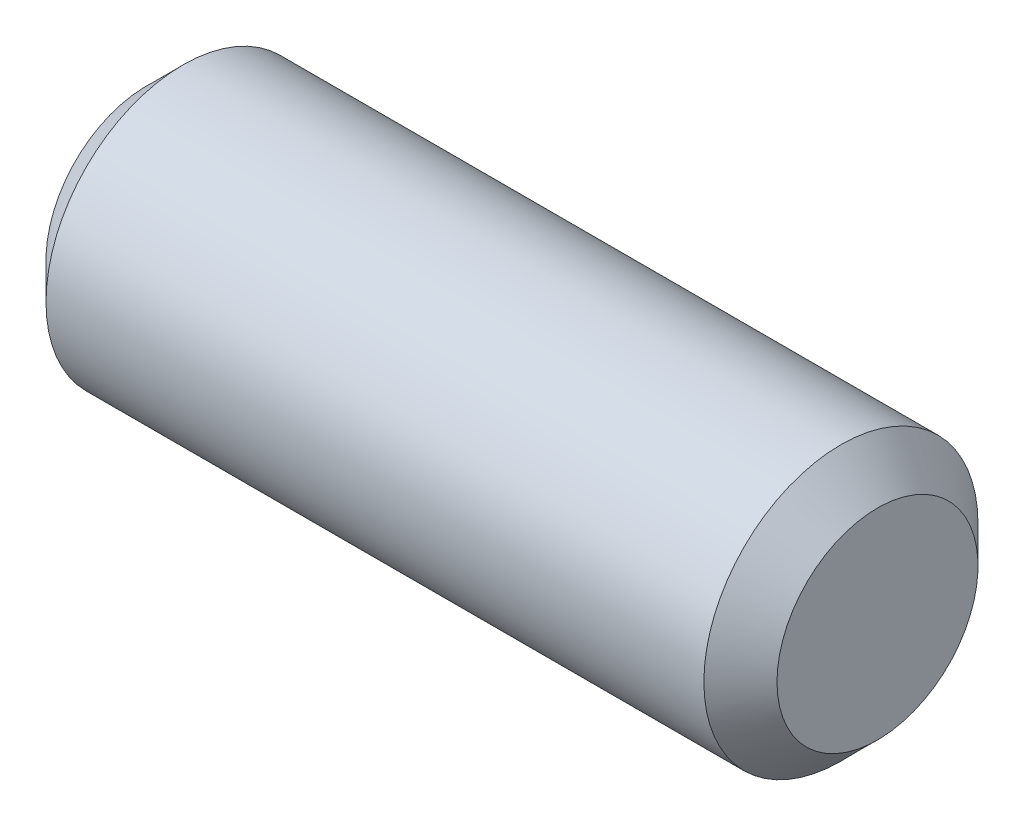
SolidWorks part; units mm, degrees
ref_plane "前视基准面" through (0, 0, 0) normal (0, 0, 1) x (1, 0, 0)
ref_plane "上视基准面" through (0, 0, 0) normal (0, 1, 0) x (1, 0, 0)
ref_plane "右视基准面" through (0, 0, 0) normal (1, 0, 0) x (0, 0, -1)
sketch "草图1" plane through (0, 0, 0) normal (0, 0, 1) x (1, 0, 0)
  line L0 (-6.3202, 0) -> (6.9944, 0) construction
  line L1 (-5.3427, 0) -> (-5.3427, 3)
  line L2 (-5.3427, 3) -> (10.6573, 3)
  line L3 (10.6573, 3) -> (10.6573, 0)
  line L4 (-5.3427, 0) -> (10.6573, 0)
  dimension "D1" = 16
  dimension "D2" = 3
revolve "旋转1" add sketch "草图1" angle 360 about L0
chamfer "倒角1" distance 0.8 angle 45 2 edges at (-5.3427, 0, 3) (10.6573, 0, 3)
